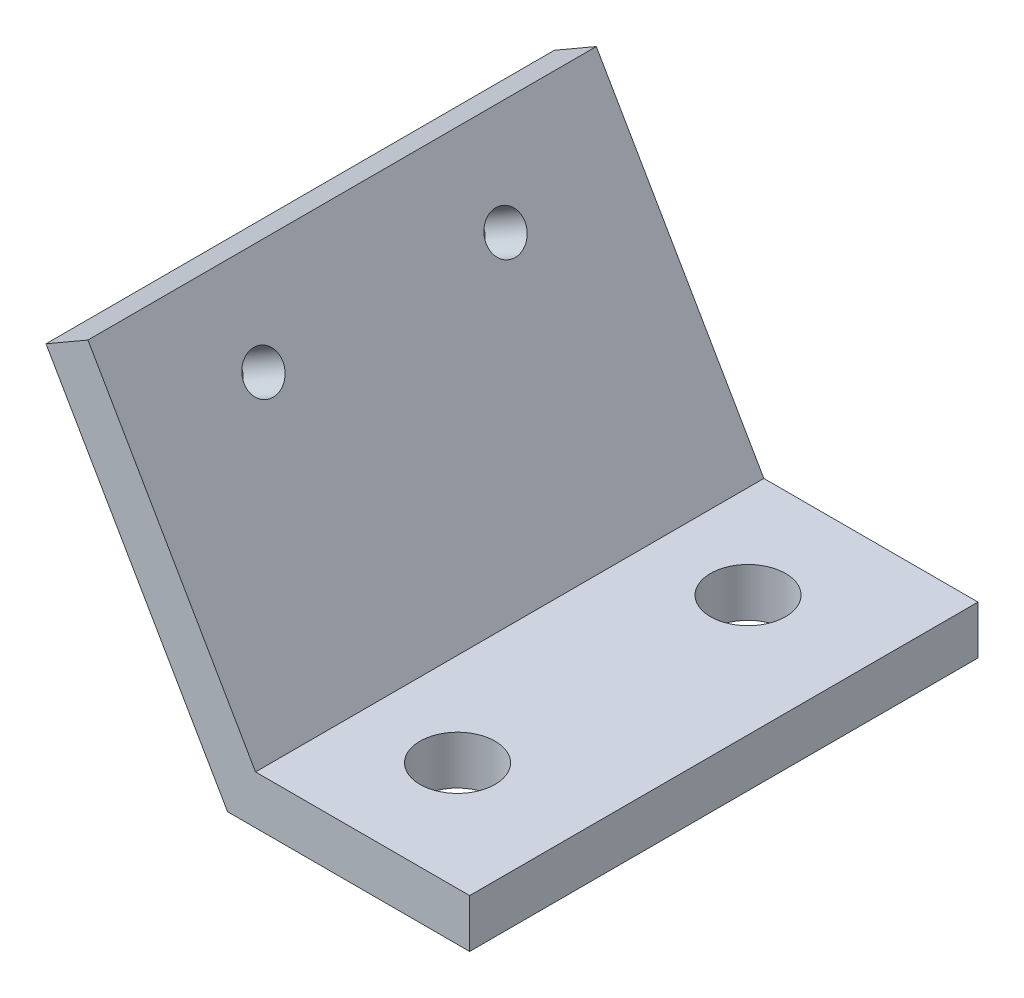
SolidWorks part; units mm, degrees
ref_plane "Front Plane" through (0, 0, 0) normal (0, 0, 1) x (1, 0, 0)
ref_plane "Top Plane" through (0, 0, 0) normal (0, 1, 0) x (1, 0, 0)
ref_plane "Right Plane" through (0, 0, 0) normal (1, 0, 0) x (0, 0, -1)
sketch "Sketch1" plane through (0, 0, 0) normal (0, 0, 1) x (1, 0, 0)
  line L0 (-32.3906, -27.7859) -> (-14.7, -27.7859)
  line L1 (-14.7, -27.7859) -> (-14.7, -31.7859)
  line L2 (-14.7, -31.7859) -> (-34.7, -31.7859)
  line L3 (-34.7, -31.7859) -> (-49.7, -5.8052)
  line L4 (-49.7, -5.8052) -> (-46.2359, -3.8052)
  line L5 (-46.2359, -3.8052) -> (-32.3906, -27.7859)
  dimension "D1" = 90
  dimension "D2" = 120
  dimension "D3" = 4
  dimension "D4" = 4
  dimension "D5" = 30
  dimension "D6" = 20
extrude "Boss-Extrude1" add sketch "Sketch1" along normal blind 42
sketch "Sketch4" plane through (-39.7887, -22.972, 0) normal (-0.866, -0.5, 0) x (0, 0, 1)
  line L1 (0, 12.8226) -> (42, 12.8226) construction
  line L2 (0, 19.8226) -> (0, -10.1774) construction
  line L3 (42, 19.8226) -> (42, -10.1774) construction
  line L4 (42, -10.1774) -> (0, -10.1774) construction
  circle A2 centre (31, 12.8226) radius 1.6
  circle A3 centre (11, 12.8226) radius 1.6
  point P12 (21, 12.8226)
  dimension "D3" = 10
  dimension "D4" = 3.2
  dimension "D5" = 3.2
  dimension "D1" = 23
  dimension "D2" = 10
extrude "Cut-Extrude1" cut sketch "Sketch4" against normal through all and the other way through all
sketch "Sketch5" plane through (0, -31.7859, 0) normal (0, -1, 0) x (1, 0, 0)
  line L0 (-24.7, 42) -> (-24.7, 0) construction
  line L1 (-34.7, 42) -> (-14.7, 42) construction
  line L2 (-34.7, 0) -> (-14.7, 0) construction
  circle A0 centre (-24.7, 33) radius 3.1
  circle A1 centre (-24.7, 9) radius 3.1
  point P10 (-24.7, 21)
  dimension "D1" = 6.2
  dimension "D2" = 6.2
  dimension "D3" = 12
  dimension "D4" = 12
extrude "Cut-Extrude2" cut sketch "Sketch5" against normal through all
